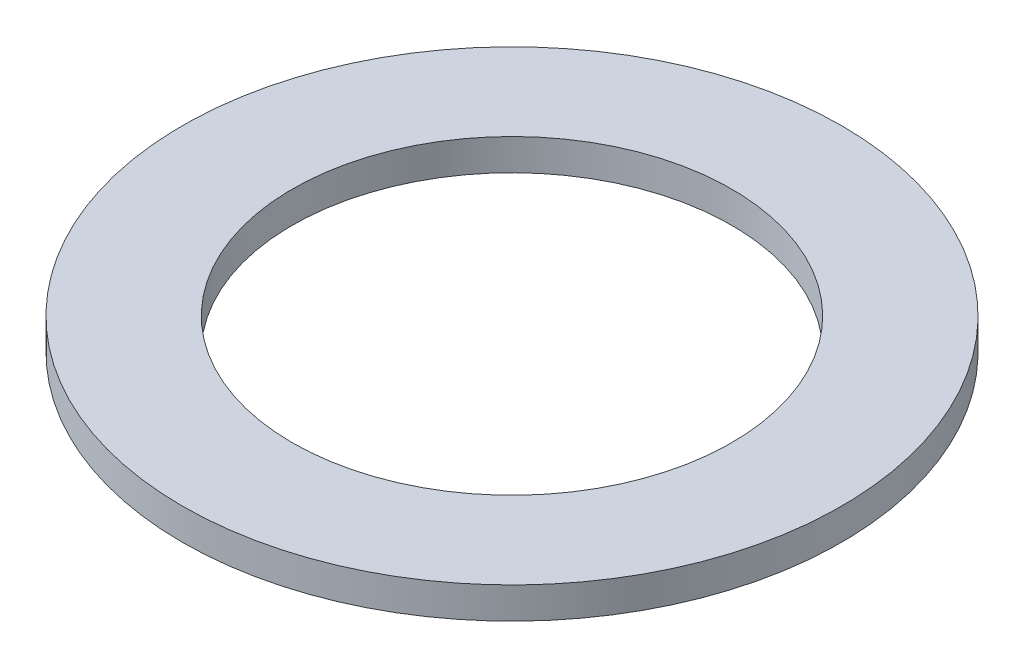
SolidWorks part; units mm, degrees
ref_plane "前视基准面" through (0, 0, 0) normal (0, 0, 1) x (1, 0, 0)
ref_plane "上视基准面" through (0, 0, 0) normal (0, 1, 0) x (1, 0, 0)
ref_plane "右视基准面" through (0, 0, 0) normal (1, 0, 0) x (0, 0, -1)
sketch "草图1" plane through (0, 0, 0) normal (0, 1, 0) x (1, 0, 0)
  circle A0 centre (0, 0) radius 10.5
  circle A1 centre (0, 0) radius 7
  dimension "D1" = 21
  dimension "D2" = 14
extrude "凸台-拉伸1" add sketch "草图1" along normal blind 1
